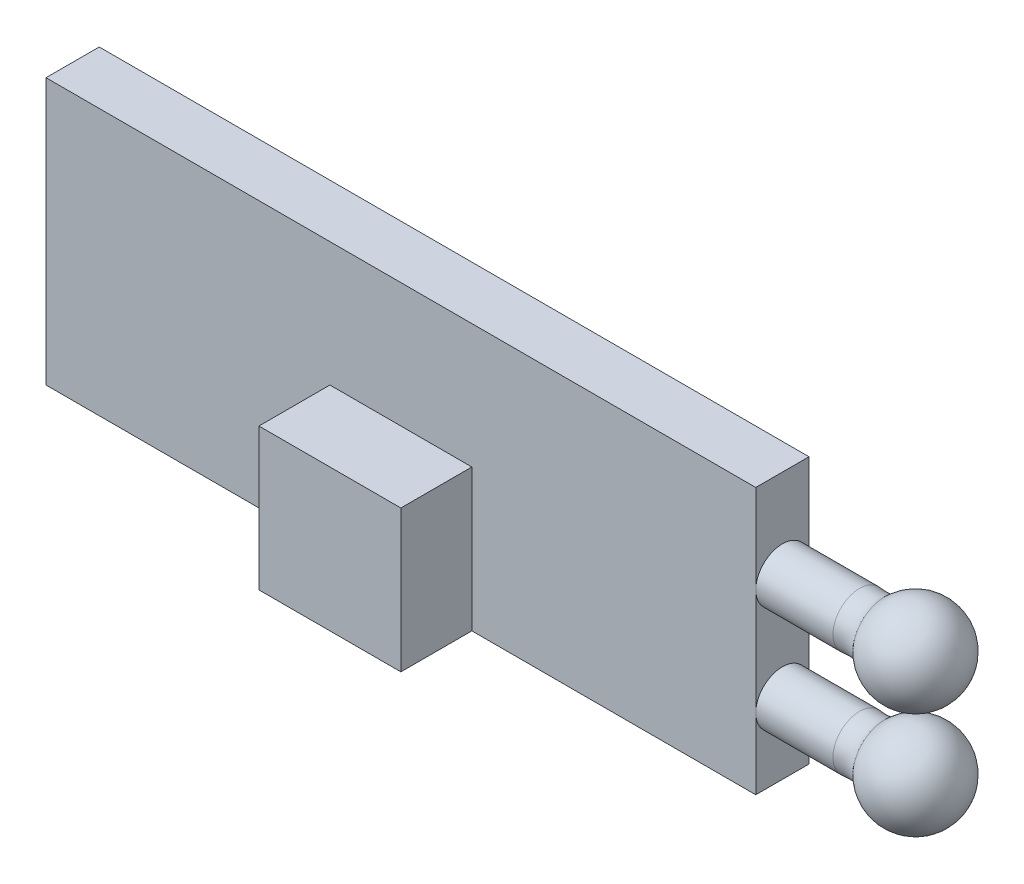
SolidWorks part; units mm, degrees
ref_plane "前视基准面" through (0, 0, 0) normal (0, 0, 1) x (1, 0, 0)
ref_plane "上视基准面" through (0, 0, 0) normal (0, 1, 0) x (1, 0, 0)
ref_plane "右视基准面" through (0, 0, 0) normal (1, 0, 0) x (0, 0, -1)
sketch "草图1" plane through (0, 0, 0) normal (0, 0, 1) x (1, 0, 0)
  line L1 (0, 0) -> (40, 0)
  line L2 (0, 0) -> (0, 15)
  line L3 (0, 15) -> (40, 15)
  line L4 (40, 0) -> (40, 15)
  dimension "D1" = 40
  dimension "D2" = 15
extrude "凸台-拉伸1" add sketch "草图1" along normal blind 3
sketch "草图2" plane through (0, 0, 3) normal (0, 0, 1) x (1, 0, 0)
  line L0 (0, 0) -> (40, 0) construction
  line L1 (16, 8) -> (24, 8)
  line L2 (16, 8) -> (16, 0)
  line L3 (16, 0) -> (24, 0)
  line L4 (24, 8) -> (24, 0)
  line L5 (0, 15) -> (0, 0) construction
  dimension "D1" = 8
  dimension "D2" = 8
  dimension "D3" = 16
extrude "凸台-拉伸2" add sketch "草图2" along normal blind 4 separate body
ref_plane "基准面1" through (0, 0, 1.5) normal (0, 0, 1) x (1, 0, 0)
sketch "草图3" plane through (0, 0, 1.5) normal (0, 0, 1) x (1, 0, 0)
  line L0 (40, 6) -> (52.5, 6) construction
  line L1 (40, 0) -> (40, 15) construction
  line L2 (40, 7.5) -> (44.3496, 7.5)
  line L3 (40, 7.5) -> (40, 6)
  line L4 (40, 6) -> (50, 6)
  arc A1 (50, 6) -> (45.7969, 7.8301) centre (47.5, 6) ccw
  spline S0 degree 3 poles (45.7969, 7.8301) (45.4824, 7.4043) (44.7852, 7.4577) (44.3496, 7.5) knots 0 0 0 0 1 1 1 1
  dimension "D1" = 2.5
  dimension "D2" = 10
  dimension "D3" = 1.5
revolve "旋转2" add sketch "草图3" angle 360 about L4
move or copy body "实体-移动/复制1" bodies to move or copy 108 copy yes number of copies 1 translate (0, 5, 0)
move or copy body "实体-移动/复制2" bodies to move or copy 109 108 copy no translate (0, -2, 0)
move or copy body "实体-移动/复制3" bodies to move or copy 110 copy no translate (0, 1, 0)
